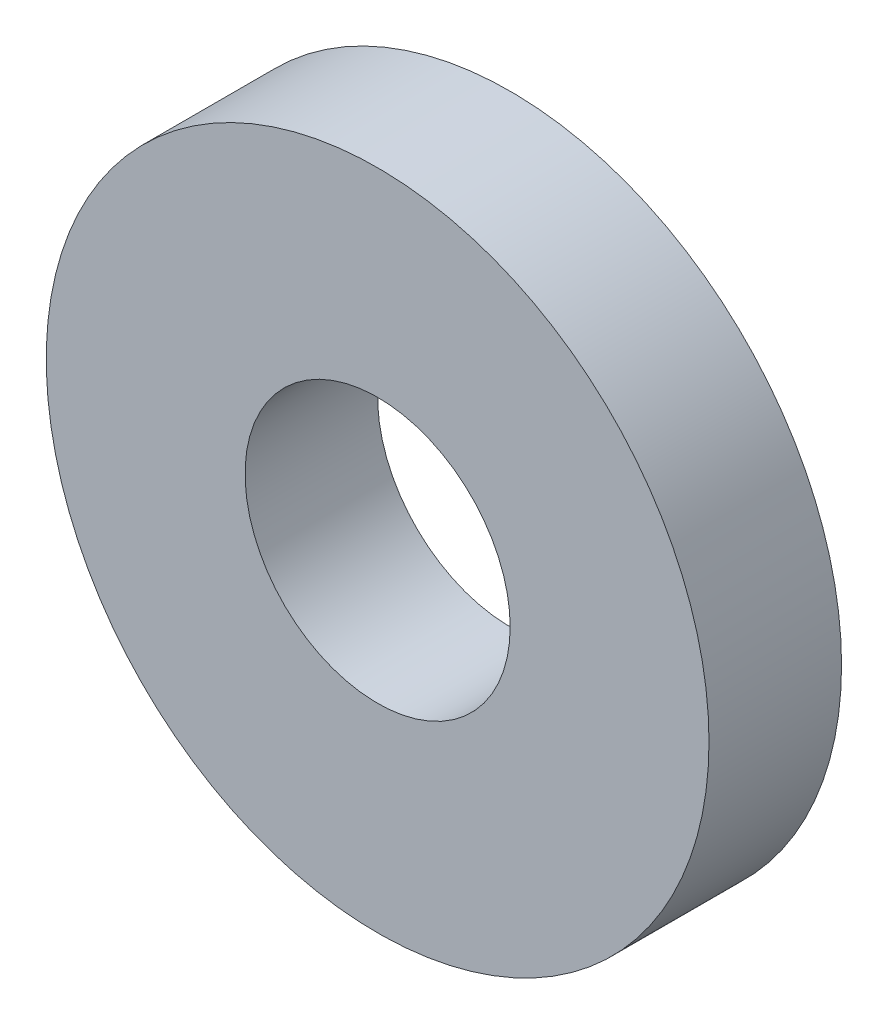
SolidWorks part; units mm, degrees
ref_plane "Front Plane" through (0, 0, 0) normal (0, 0, 1) x (1, 0, 0)
ref_plane "Top Plane" through (0, 0, 0) normal (0, 1, 0) x (1, 0, 0)
ref_plane "Right Plane" through (0, 0, 0) normal (1, 0, 0) x (0, 0, -1)
sketch "Sketch1" plane through (0, 0, 0) normal (0, 0, 1) x (1, 0, 0)
  circle A0 centre (0, 0) radius 5
  circle A1 centre (0, 0) radius 12.5
  dimension "D1" = 10
  dimension "D2" = 25
extrude "Boss-Extrude1" add sketch "Sketch1" along normal blind 5
